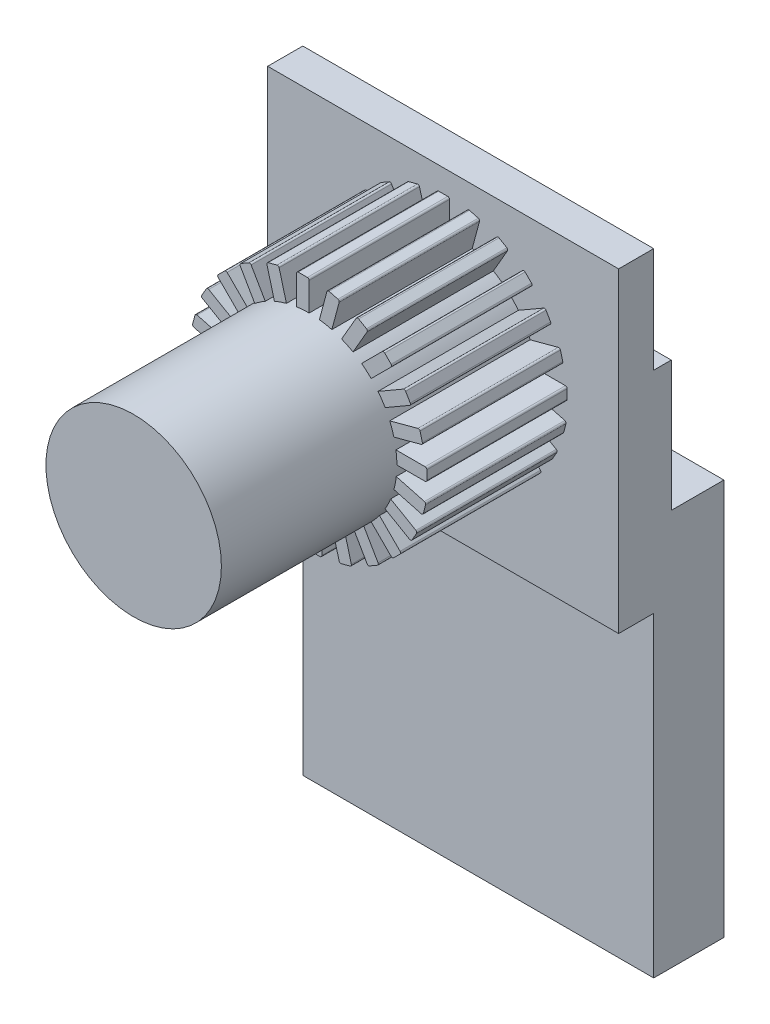
SolidWorks part; units mm, degrees
ref_plane "Front Plane" through (0, 0, 0) normal (0, 0, 1) x (1, 0, 0)
ref_plane "Top Plane" through (0, 0, 0) normal (0, 1, 0) x (1, 0, 0)
ref_plane "Right Plane" through (0, 0, 0) normal (1, 0, 0) x (0, 0, -1)
sketch "Sketch1" plane through (0, 0, 0) normal (0, 0, 1) x (1, 0, 0)
  line L0 (4.0523, 133.3333) -> (-1.1765, 69.281)
  line L1 (-85.9477, 133.3333) -> (114.0523, 133.3333)
  line L2 (-85.9477, 133.3333) -> (-85.9477, -166.6667)
  line L3 (-85.9477, -166.6667) -> (114.0523, -166.6667)
  line L4 (114.0523, 133.3333) -> (114.0523, -166.6667)
  line L5 (-1.1765, 69.281) -> (-85.9477, 69.281)
  line L6 (24.0523, 133.3333) -> (31.8954, 69.281)
  line L7 (31.8954, 69.281) -> (114.0523, 69.281)
  line L8 (114.0523, 69.281) -> (114.0523, 133.3333)
  line L9 (24.0523, 133.3333) -> (114.0523, 133.3333)
  line L10 (-85.9477, 69.281) -> (-85.9477, 133.3333)
  line L11 (4.0523, 133.3333) -> (-85.9477, 133.3333)
  line L12 (114.0523, 133.3333) -> (24.0523, 133.3333)
  line L13 (31.8954, 69.281) -> (114.0523, 69.281)
  line L14 (4.0523, 133.3333) -> (-1.1765, 69.281)
  line L15 (-85.9477, 69.281) -> (-85.9477, 133.3333)
  dimension "D1" = 200
  dimension "D2" = 300
  dimension "D3" = 90
  dimension "D4" = 90
extrude "Boss-Extrude1" add sketch "Sketch1" along normal blind 40 contours L7 L6 L1 L0 L5 L2 L3 L4 | L5 L0 L1 L2 | L6 L7 L4 L1
sketch "Sketch2" plane through (0, 0, 0) normal (0, 0, -1) x (-1, 0, 0)
  line L0 (-24.0523, 133.3333) -> (-39.8434, 59.1233)
  line L1 (85.9477, 133.3333) -> (-114.0523, 133.3333) construction
  line L2 (-39.8434, 59.1233) -> (-114.0523, 59.1233)
  line L3 (-114.0523, 133.3333) -> (-114.0523, -166.6667) construction
  line L4 (-114.0523, 59.1233) -> (-114.0523, 133.3333)
  line L5 (-114.0523, 133.3333) -> (-24.0523, 133.3333)
  line L6 (-4.0523, 133.3333) -> (7.8441, 59.1233)
  line L7 (7.8441, 59.1233) -> (85.9477, 59.1233)
  line L8 (85.9477, 133.3333) -> (85.9477, -166.6667) construction
  line L9 (85.9477, 59.1233) -> (85.9477, 133.3333)
  line L10 (85.9477, 133.3333) -> (-4.0523, 133.3333)
  dimension "D1" = 90
  dimension "D2" = 90
extrude "Cut-Extrude2" cut sketch "Sketch2" against normal blind 30
sketch "Sketch3" plane through (0, 0, 40) normal (0, 0, 1) x (1, 0, 0)
  line L0 (-85.9477, 133.3333) -> (-85.9477, -166.6667) construction
  line L1 (-85.9477, 13.3333) -> (114.0523, 13.3333)
  line L2 (-85.9477, 13.3333) -> (-85.9477, 193.3333)
  line L3 (-85.9477, 193.3333) -> (114.0523, 193.3333)
  line L4 (114.0523, 13.3333) -> (114.0523, 193.3333)
  dimension "D1" = 200
  dimension "D2" = 180
  dimension "D3" = 120
extrude "Boss-Extrude2" add sketch "Sketch3" along normal blind 20
sketch "Sketch5" plane through (-16.888, 2.7073, 0) normal (-0.9874, 0.1583, 0) x (0, 0, 1)
  circle A0 centre (18.4777, 99.2085) radius 7.5472
extrude "Cut-Extrude5" cut sketch "Sketch5" along direction (1, 0, 0) on the side against the normal blind 40
sketch "Sketch6" plane through (0, 0, 60) normal (0, 0, 1) x (1, 0, 0)
  line L0 (114.0523, 193.3333) -> (-85.9477, 193.3333) construction
  circle A0 centre (17.6709, 113.3333) radius 50
  dimension "D1" = 80
extrude "Boss-Extrude3" add sketch "Sketch6" along normal blind 80 contours A0
sketch "Sketch7" plane through (0, 0, 140) normal (0, 0, 1) x (1, 0, 0)
  line L1 (10.4681, 162.8118) -> (17.6709, 162.8118)
  line L2 (10.4681, 162.8118) -> (10.4681, 179.4244)
  line L3 (11.4681, 180.4244) -> (16.6709, 180.4244)
  line L4 (17.6709, 162.8118) -> (17.6709, 179.4244)
  circle A0 centre (17.6709, 113.3333) radius 50 construction
  arc A1 (16.6709, 180.4244) -> (17.6709, 179.4244) centre (16.6709, 179.4244) cw
  arc A2 (10.4681, 179.4244) -> (11.4681, 180.4244) centre (11.4681, 179.4244) cw
  dimension "D1" = 1
extrude "Boss-Extrude5" add sketch "Sketch7" against normal blind 80
pattern_circular "CirPattern1" count 24 over 360 about axis through (17.6709, 113.3333, 0) along (0, 0, 1) of "Boss-Extrude5"
ref_plane "Plane2" through (0, 0, 240) normal (0, 0, 1) x (1, 0, 0)
sketch "Sketch11" plane through (0, 0, 240) normal (0, 0, 1) x (1, 0, 0)
  circle A1 centre (17.6709, 113.3333) radius 50
extrude "Boss-Extrude6" add sketch "Sketch11" against normal blind 100
ref_plane "Plane3" through (84.0523, 0, 0) normal (1, 0, 0) x (0, 0, -1)
sketch "Sketch12" plane through (84.762, 0, 0) normal (1, 0, 0) x (0, 0, -1)
  line L0 (-140, 119.5361) -> (-185.7474, 119.5361)
  line L1 (-185.7474, 119.5361) -> (-185.7474, 176.2752)
  line L2 (-185.7474, 176.2752) -> (-63.8167, 176.2752)
  line L3 (-63.8167, 176.2752) -> (-60, 119.5361)
  line L4 (-60, 119.5361) -> (-56.073, 61.1567)
  line L5 (-56.073, 61.1567) -> (-185.7474, 52.4338)
  line L6 (-185.7474, 52.4338) -> (-185.7474, 119.5361)
